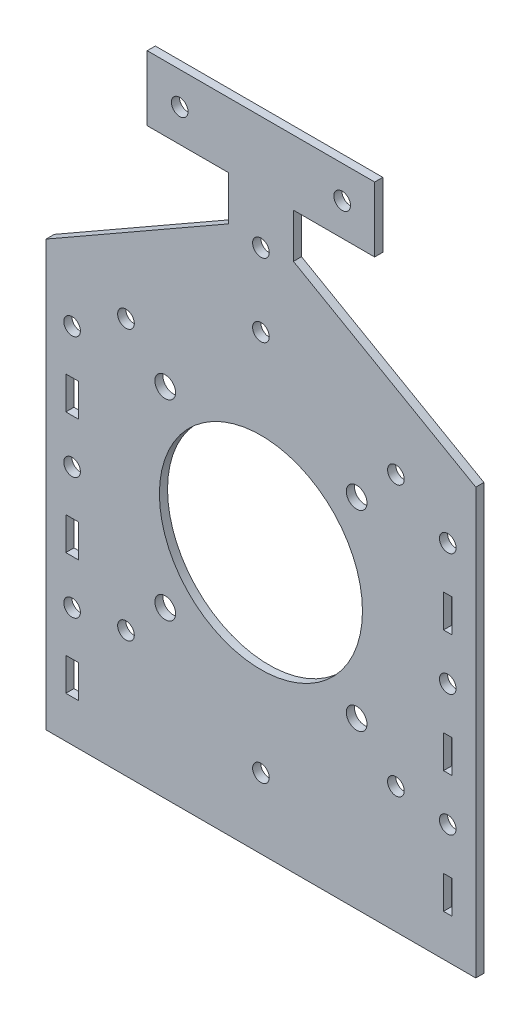
SolidWorks part; units mm, degrees
ref_plane "前视基准面" through (0, 0, 0) normal (0, 0, 1) x (1, 0, 0)
ref_plane "上视基准面" through (0, 0, 0) normal (0, 1, 0) x (1, 0, 0)
ref_plane "右视基准面" through (0, 0, 0) normal (1, 0, 0) x (0, 0, -1)
sketch "草图1" plane through (0, 0, 0) normal (0, 0, 1) x (1, 0, 0)
  line L0 (0, -36.5) -> (-46, -36.5) construction
  line L29 (-52.9, 53.8832) -> (-52.9, -50.79)
  line L32 (0, 63.5) -> (0, -36.5) construction
  line L33 (-23.57, 37.07) -> (-23.57, -10.07) construction
  line L34 (23.57, 37.07) -> (23.57, -10.07) construction
  line L38 (52.9, 53.8832) -> (52.9, -50.79)
  line L52 (-52.9, 53.8832) -> (52.9, 53.8832) construction
  line L53 (52.9, -50.79) -> (-52.9, -50.79)
  line L60 (0, 78.5) -> (0, 84.5) construction
  line L61 (-28, 106.5) -> (28, 106.5)
  line L62 (28, 106.5) -> (28, 90.5)
  line L63 (28, 90.5) -> (8, 90.5)
  line L64 (8, 90.5) -> (8, 79.5697)
  line L65 (-28, 106.5) -> (-28, 90.5)
  line L66 (-28, 90.5) -> (-8, 90.5)
  line L67 (-8, 90.5) -> (-8, 79.5697)
  line L76 (-52.9, 53.8832) -> (-8, 79.5697)
  line L77 (8, 79.5697) -> (52.9, 53.8832)
  line L78 (46, 8.5) -> (43.95, 8.5) construction
  line L79 (47.05, 19.45) -> (44.95, 27.55) construction
  line L80 (47.05, 27.55) -> (44.95, 19.45) construction
  line L81 (46, -6.5) -> (44.95, -6.5) construction
  line L82 (47.05, -10.55) -> (44.95, -2.45) construction
  line L83 (47.05, -2.45) -> (44.95, -10.55) construction
  line L84 (47.05, -40.55) -> (44.95, -32.45) construction
  line L85 (47.05, -32.45) -> (44.95, -40.55) construction
  line L86 (46, -21.5) -> (43.95, -21.5) construction
  line L87 (47.05, 19.45) -> (44.95, 19.45)
  line L88 (47.05, 19.45) -> (47.05, 27.55)
  line L89 (47.05, 27.55) -> (44.95, 27.55)
  line L90 (44.95, 19.45) -> (44.95, 27.55)
  line L91 (47.05, -10.55) -> (44.95, -10.55)
  line L92 (47.05, -10.55) -> (47.05, -2.45)
  line L93 (47.05, -2.45) -> (44.95, -2.45)
  line L94 (44.95, -10.55) -> (44.95, -2.45)
  line L95 (44.95, -32.45) -> (44.95, -40.55)
  line L96 (47.05, -40.55) -> (44.95, -40.55)
  line L97 (47.05, -32.45) -> (47.05, -40.55)
  line L98 (47.05, -32.45) -> (44.95, -32.45)
  line L101 (-44.95, 27.55) -> (-48.05, 27.55)
  line L139 (-44.95, 19.45) -> (-48.05, 19.45)
  line L140 (-44.95, 27.55) -> (-44.95, 19.45)
  line L141 (-48.05, 27.55) -> (-48.05, 19.45)
  line L142 (-44.95, -2.45) -> (-44.95, -10.55)
  line L143 (-44.95, -10.55) -> (-48.05, -10.55)
  line L144 (-44.95, -2.45) -> (-48.05, -2.45)
  line L145 (-48.05, -2.45) -> (-48.05, -10.55)
  line L146 (-44.95, -32.45) -> (-48.05, -32.45)
  line L147 (-44.95, -40.55) -> (-48.05, -40.55)
  line L148 (-44.95, -32.45) -> (-44.95, -40.55)
  line L149 (-48.05, -32.45) -> (-48.05, -40.55)
  circle A7 centre (-23.57, 37.07) radius 2.55
  circle A10 centre (-23.57, -10.07) radius 2.55
  circle A11 centre (23.57, -10.07) radius 2.55
  circle A12 centre (23.57, 37.07) radius 2.55
  circle A16 centre (0, 13.5) radius 25
  circle A17 centre (0, 13.5) radius 47 construction
  circle A18 centre (0, 60.5) radius 2.05
  circle A41 centre (33.234, 46.734) radius 2.05
  circle A43 centre (33.234, -19.734) radius 2.05
  circle A44 centre (0, -33.5) radius 2.05
  circle A45 centre (-33.234, -19.734) radius 2.05
  circle A47 centre (-33.234, 46.734) radius 2.05
  circle A48 centre (0, 78.5) radius 2.05
  circle A50 centre (-20, 98.5) radius 2.05
  circle A51 centre (20, 98.5) radius 2.05
  circle A52 centre (-47, 13.5) radius 2.05 construction
  circle A53 centre (47, 13.5) radius 2.05 construction
  circle A56 centre (46, 8.5) radius 2.05
  circle A57 centre (46, -21.5) radius 2.05
  circle A59 centre (46, 38.5) radius 2.05
  circle A63 centre (-46.5, -21.5) radius 2.05
  circle A64 centre (-46.5, 8.5) radius 2.05
  circle A65 centre (-46.5, 38.5) radius 2.05
  dimension "D3" = 5.1
  dimension "D6" = 23.57
  dimension "D8" = 64.29
  dimension "D10" = 65
  dimension "D16" = 4.1
  dimension "D27" = 50
  dimension "D4" = 46
  dimension "D5" = 8
  dimension "D7" = 47.14
  dimension "D12" = 50
  dimension "D17" = 20
  dimension "D18" = 20
  dimension "D19" = 20
  dimension "D20" = 20
  dimension "D21" = 8
  dimension "D22" = 8
  dimension "D23" = 8
  dimension "D24" = 8
  dimension "D25" = 8
  dimension "D26" = 8
extrude "凸台-拉伸1" add sketch "草图1" along normal blind 2
